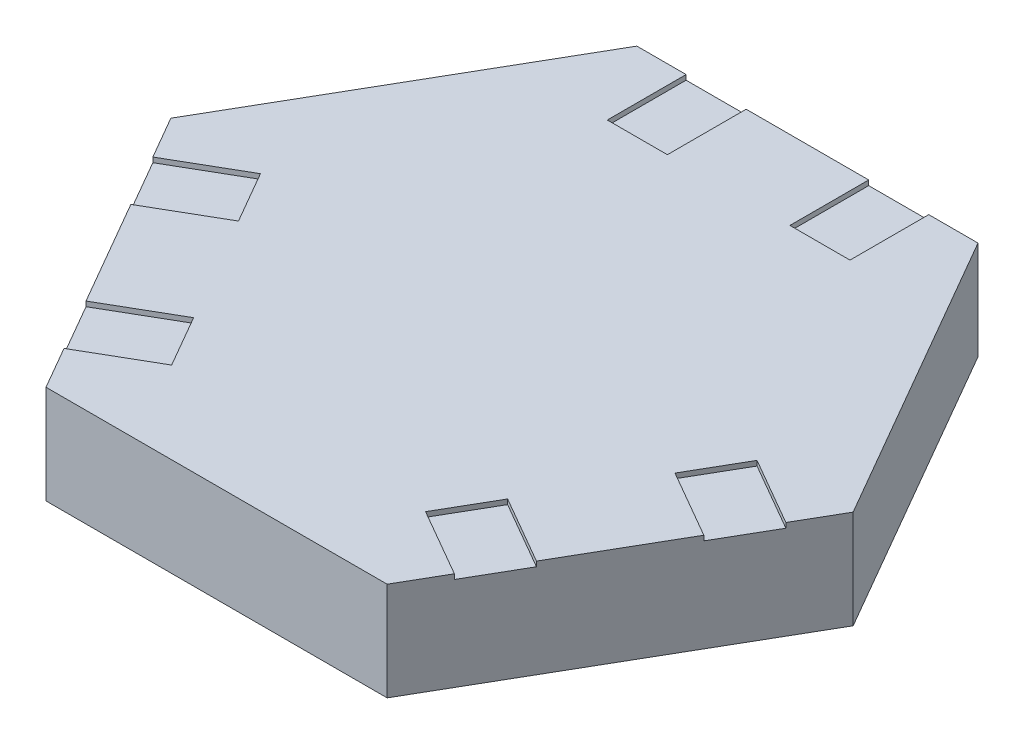
SolidWorks part; units mm, degrees
ref_plane "Front Plane" through (0, 0, 0) normal (0, 0, 1) x (1, 0, 0)
ref_plane "Top Plane" through (0, 0, 0) normal (0, 1, 0) x (1, 0, 0)
ref_plane "Right Plane" through (0, 0, 0) normal (1, 0, 0) x (0, 0, -1)
sketch "Sketch1" plane through (0, 0, 0) normal (0, 1, 0) x (1, 0, 0)
  line L0 (0, 0) -> (39.7226, 0) construction
  line L1 (0, 0) -> (0, 31.3322) construction
  line L3 (69.282, 0) -> (34.641, 60)
  line L4 (34.641, 60) -> (-34.641, 60)
  line L5 (-34.641, 60) -> (-69.282, 0)
  line L6 (-69.282, 0) -> (-34.641, -60)
  line L7 (-34.641, -60) -> (34.641, -60)
  line L8 (34.641, -60) -> (69.282, 0)
  circle A1 centre (0, 0) radius 60 construction
  dimension "D1" = 120
extrude "Boss-Extrude1" add sketch "Sketch1" along normal blind 20
sketch "Sketch2" plane through (0, 20, 0) normal (0, 1, 0) x (1, 0, 0)
  line L0 (-24.641, 60) -> (-24.641, 44)
  line L1 (34.641, 60) -> (-34.641, 60) construction
  line L2 (-24.641, 44) -> (-12.441, 44)
  line L3 (-12.441, 44) -> (-12.441, 60)
  line L4 (12.441, 60) -> (12.441, 44)
  line L5 (12.441, 44) -> (24.641, 44)
  line L6 (24.641, 44) -> (24.641, 60)
  line L7 (64.282, -8.6603) -> (50.4256, -0.6603)
  line L8 (50.4256, -0.6603) -> (44.3256, -11.2258)
  line L9 (44.3256, -11.2258) -> (58.182, -19.2258)
  line L10 (45.741, -40.7742) -> (31.8846, -32.7742)
  line L11 (31.8846, -32.7742) -> (25.7846, -43.3397)
  line L12 (25.7846, -43.3397) -> (39.641, -51.3397)
  line L13 (-39.641, -51.3397) -> (-25.7846, -43.3397)
  line L14 (-25.7846, -43.3397) -> (-31.8846, -32.7742)
  line L15 (-31.8846, -32.7742) -> (-45.741, -40.7742)
  line L16 (-58.182, -19.2258) -> (-44.3256, -11.2258)
  line L17 (-44.3256, -11.2258) -> (-50.4256, -0.6603)
  line L18 (-50.4256, -0.6603) -> (-64.282, -8.6603)
  line L19 (-24.641, 60) -> (-12.441, 60)
  line L20 (12.441, 60) -> (24.641, 60)
  line L21 (64.282, -8.6603) -> (58.182, -19.2258)
  line L22 (45.741, -40.7742) -> (39.641, -51.3397)
  line L23 (-45.741, -40.7742) -> (-39.641, -51.3397)
  line L24 (-64.282, -8.6603) -> (-58.182, -19.2258)
  point P10 (-12.441, 52)
  point P11 (24.641, 52)
  dimension "D1" = 10
  dimension "D2" = 10
  dimension "D3" = 12.2
  dimension "D4" = 12.2
  dimension "D5" = 16
  dimension "D6" = 16
  dimension "D7" = 3
extrude "Cut-Extrude1" cut sketch "Sketch2" against normal blind 1
equation "\"D2@Sketch2\"=\"D1@Sketch2\""
equation "\"D4@Sketch2\"=\"D3@Sketch2\""
equation "\"D6@Sketch2\"=\"D5@Sketch2\""
